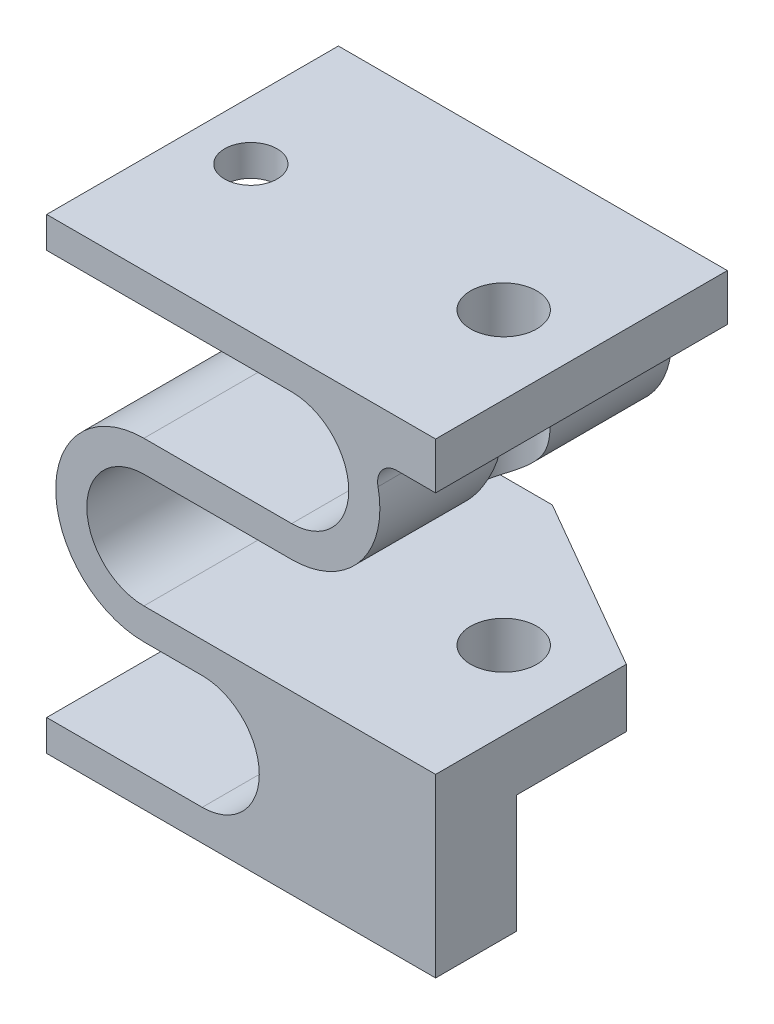
SolidWorks part; units mm, degrees
ref_plane "Front Plane" through (0, 0, 0) normal (0, 0, 1) x (1, 0, 0)
ref_plane "Top Plane" through (0, 0, 0) normal (0, 1, 0) x (1, 0, 0)
ref_plane "Right Plane" through (0, 0, 0) normal (1, 0, 0) x (0, 0, -1)
sketch "Sketch1" plane through (0, 0, 0) normal (0, 0, 1) x (1, 0, 0)
  line L0 (2.0427, 12) -> (46.3243, 12) construction
  line L1 (0, 0) -> (20, 0)
  line L2 (0, 0) -> (0, 1.6)
  line L3 (0, 1.6) -> (8, 1.6)
  line L4 (20, 0) -> (20, 9.0664)
  line L5 (5, 14.933) -> (12.6, 14.933)
  line L6 (0, 22.4) -> (12.6, 22.4)
  line L7 (0, 24) -> (0, 22.4)
  line L8 (0, 24) -> (20, 24.0007)
  line L9 (8, 9.0664) -> (20, 9.0664)
  line L10 (5, 9.0664) -> (8, 9.0664)
  line L12 (5, 7.4661) -> (8, 7.4661)
  line L13 (5, 16.5335) -> (12.6, 16.5335)
  line L14 (20, 24.0007) -> (20, 21.6001)
  line L15 (20, 21.6001) -> (18.0164, 21.6001)
  arc A0 (12.6, 16.5335) -> (12.6, 22.4) centre (12.6, 19.4667) ccw
  arc A1 (12.6, 14.933) -> (17.0376, 20.3953) centre (12.6, 19.4667) ccw
  arc A2 (5, 14.933) -> (5, 9.0664) centre (5, 11.9997) ccw
  arc A4 (5, 16.5335) -> (5, 7.4661) centre (5, 11.9998) ccw
  arc A5 (8, 7.4661) -> (8, 1.6) centre (8, 4.533) cw
  arc A11 (17.0376, 20.3953) -> (18.0164, 21.6001) centre (18.0164, 20.6001) cw
  point P3 (7.9095, 0)
  point P12 (8, 4.5327)
  dimension "D4" = 1
  dimension "D5" = 12.6
  dimension "D1" = 8
  dimension "D2" = 1.6
  dimension "D3" = 12
  dimension "D7" = 20
  dimension "D8" = 5
extrude "Boss-Extrude1" add sketch "Sketch1" along normal blind 15
sketch "Sketch2" plane through (-0.0009, 24, 0) normal (0, 1, 0) x (1, 0, 0)
  line L0 (0.0009, -7.5) -> (46.5982, -7.5) construction
  line L1 (0.0009, -15) -> (0.0009, 0) construction
  circle A0 centre (16.0009, -7.5) radius 1.7
  dimension "D1" = 3.4
  dimension "D3" = 16
extrude "Cut-Extrude1" cut sketch "Sketch2" against normal through all
sketch "Sketch3" plane through (0, 0, 0) normal (0, -1, 0) x (1, 0, 0)
  line L0 (21.0854, -1.0901) -> (21.0854, 10.8486)
  line L1 (16.0009, 7.5) -> (16.0006, 7.5) construction
  line L2 (13.1009, 9.1743) -> (13.1009, -1.0901)
  line L3 (13.1009, -1.0901) -> (21.0854, -1.0901)
  line L4 (16.0009, 7.5) -> (27.5689, 7.5) construction
  line L6 (13.1009, 9.1743) -> (16.0009, 10.8486)
  line L8 (16.0009, 10.8486) -> (21.0854, 10.8486)
  circle A0 centre (16.0009, 7.5) radius 2.9 construction
  circle A2 centre (16.0009, 7.5) radius 1.7 construction
  dimension "D1" = 5.8
extrude "Cut-Extrude2" cut sketch "Sketch3" against normal offset from surface (6.0664 mm away) 3 up to face at (14.3006, 9.0664, 7.5)
sketch "Sketch4" plane through (-0.0009, 24, 0) normal (0, 1, 0) x (1, 0, 0)
  line L0 (20.0009, -7.5) -> (0.0009, -7.5) construction
  line L1 (20.0009, -15) -> (20.0009, 0) construction
  line L2 (0.0009, -15) -> (0.0009, 0) construction
  circle A0 centre (3.0009, -7.5) radius 1.35
  dimension "D2" = 2.7
  dimension "D1" = 3
extrude "Cut-Extrude3" cut sketch "Sketch4" against normal up to next
sketch "Sketch5" plane through (0, 0, 0) normal (0, -1, 0) x (1, 0, 0)
  circle A0 centre (3.0001, 7.5) radius 1.35
  circle A1 centre (3.0001, 7.5) radius 1.35 construction
extrude "Cut-Extrude4" cut sketch "Sketch5" against normal up to next
chamfer "Chamfer2" distance 9 angle 30 1 edges at (20, 7.5664, 0)
